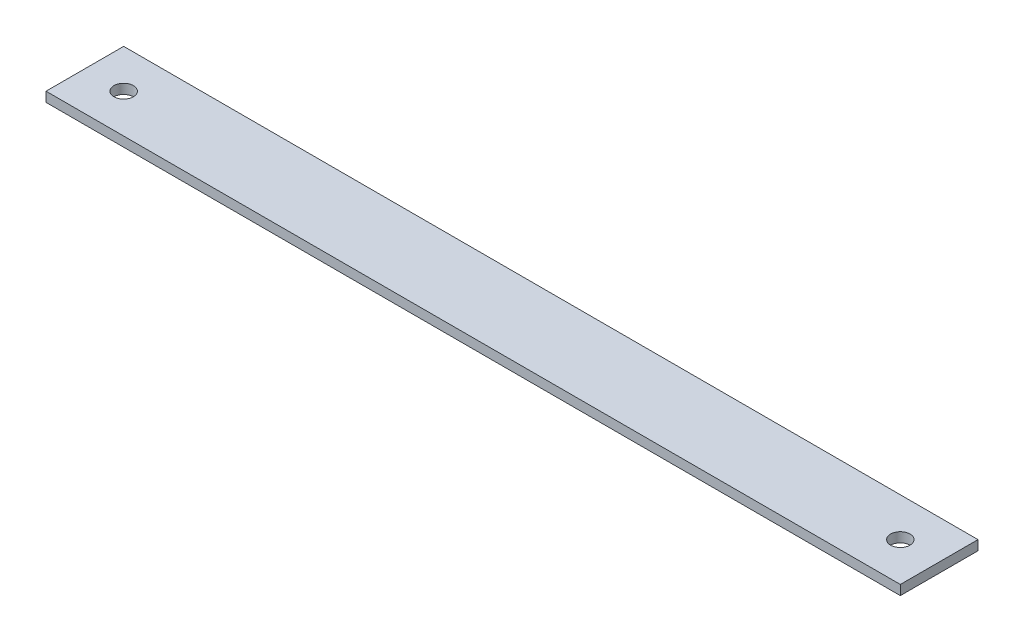
SolidWorks part; units mm, degrees
material "6061-T6 (SS)"
ref_plane "Front Plane" through (0, 0, 0) normal (0, 0, 1) x (1, 0, 0)
ref_plane "Top Plane" through (0, 0, 0) normal (0, 1, 0) x (1, 0, 0)
ref_plane "Right Plane" through (0, 0, 0) normal (1, 0, 0) x (0, 0, -1)
sketch "Sketch1" plane through (0, 0, 0) normal (0, 1, 0) x (1, 0, 0)
  line L1 (-139.7, 12.7) -> (139.7, 12.7)
  line L2 (-139.7, 12.7) -> (-139.7, -12.7)
  line L3 (-139.7, -12.7) -> (139.7, -12.7)
  line L4 (139.7, 12.7) -> (139.7, -12.7)
  line L5 (-139.7, 12.7) -> (139.7, -12.7) construction
  line L6 (-139.7, -12.7) -> (139.7, 12.7) construction
  point P0 (0, 0)
  dimension "D1" = 25.4
  dimension "D2" = 279.4
extrude "Boss-Extrude1" add sketch "Sketch1" along normal blind 3.175
sketch "Sketch2" plane through (0, 3.175, 0) normal (0, 1, 0) x (1, 0, 0)
  line L0 (0, 12.7) -> (0, -12.7) construction
  line L1 (139.7, 12.7) -> (-139.7, 12.7) construction
  line L2 (-139.7, -12.7) -> (139.7, -12.7) construction
  line L3 (-139.7, 12.7) -> (-139.7, -12.7) construction
  circle A0 centre (-127, 0) radius 3.175
  circle A1 centre (127, 0) radius 3.175
  dimension "D1" = 6.35
  dimension "D2" = 12.7
  dimension "D3" = 12.7
extrude "Cut-Extrude1" cut sketch "Sketch2" against normal up to next
